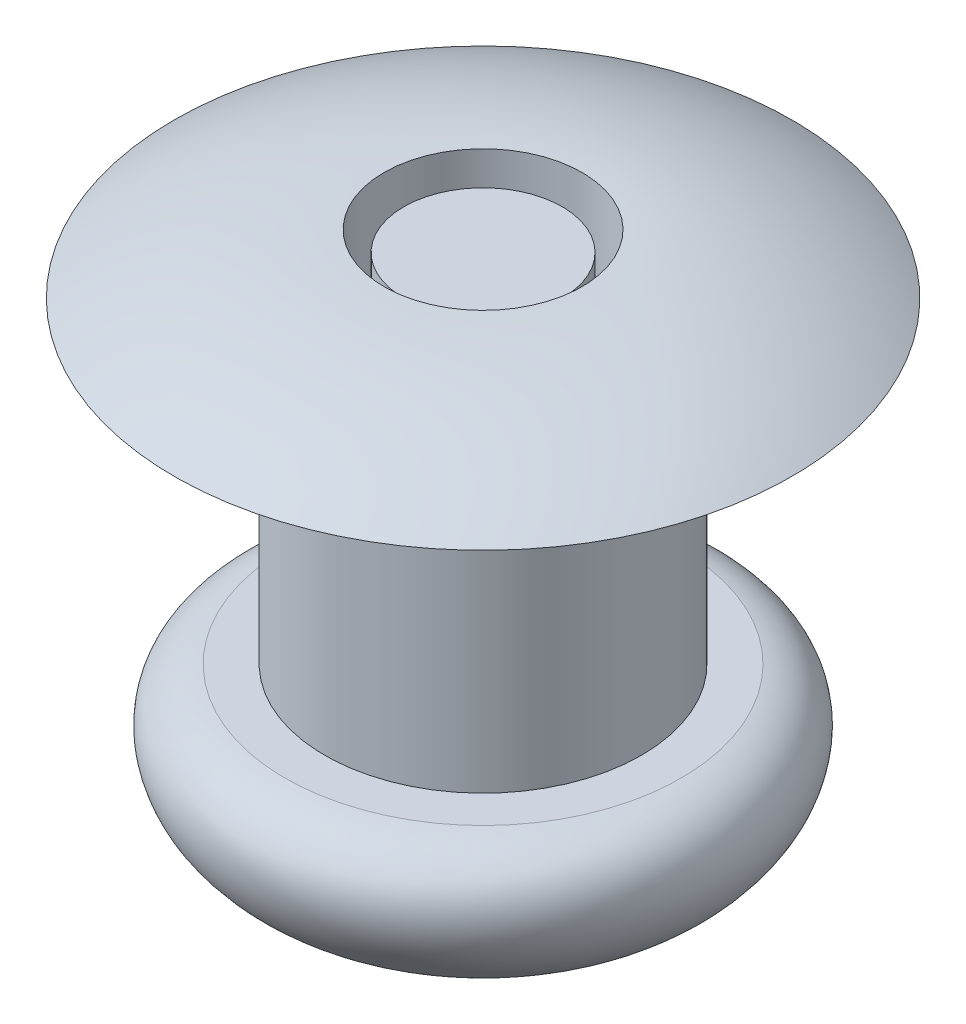
SolidWorks part; units mm, degrees
material "AISI 316 Arkusz stali nierdzewnej (SS)"
ref_plane "Płaszczyzna przednia" through (0, 0, 0) normal (0, 0, 1) x (1, 0, 0)
ref_plane "Płaszczyzna górna" through (0, 0, 0) normal (0, 1, 0) x (1, 0, 0)
ref_plane "Płaszczyzna prawa" through (0, 0, 0) normal (1, 0, 0) x (0, 0, -1)
sketch "Szkic1" plane through (0, 0, 0) normal (0, 0, 1) x (1, 0, 0)
  line L0 (0, 0) -> (0, 0.724) construction
  line L1 (-3.9, 0) -> (-2, 0)
  line L2 (-1.25, 0.75) -> (-1.25, -4)
  line L3 (-2, 0) -> (-2, -4)
  line L4 (-1.25, -4) -> (-1, -4)
  line L5 (-1, -4) -> (-1, 0.5)
  line L6 (-1, 0.5) -> (0, 0.5)
  line L7 (-2, -4) -> (-2.5, -4)
  line L8 (0, 0) -> (0, -5.4215) construction
  line L9 (0, 0.5) -> (0, -5.4215) construction
  line L10 (0, 0.5) -> (0, -5.4215)
  line L15 (6.75, -4) -> (-15.25, -4) construction
  arc A0 (-1.25, 0.75) -> (-3.9, 0) centre (-1.25, -4.3067) ccw
  spline S0 degree 3 poles (-2.5, -4) (-3.3276, -4.1478) (-3.2549, -5.9654) (-0.0301, -6.3768) (-1.229, -4.325) (-0.2169, -5.4912) (0, -5.4215) knots 0 0 0 0 0.343812 0.687239 0.819799 1 1 1 1
  point P7 (-0.8575, -2.9562)
  point P18 (-0.8575, -2.8579)
  dimension "D1" = 7.8
  dimension "D2" = 0.75
  dimension "D3" = 4
  dimension "D4" = 2.5
  dimension "D5" = 0.5
  dimension "D6" = 2
  dimension "D7" = 5
  dimension "D8" = 1.5978
  dimension "D9" = 0.3519
  dimension "D10" = 1.5835
  dimension "D11" = 1.2582
  dimension "D12" = 1.4215
  dimension "D13" = 0.8591
  dimension "D14" = 0.7171
  dimension "D15" = 1.256
  dimension "D16" = 1.715
  dimension "D17" = 5.1929
  dimension "D18" = 6.0862
revolve "Obrót1" add sketch "Szkic1" angle 360 about L9
